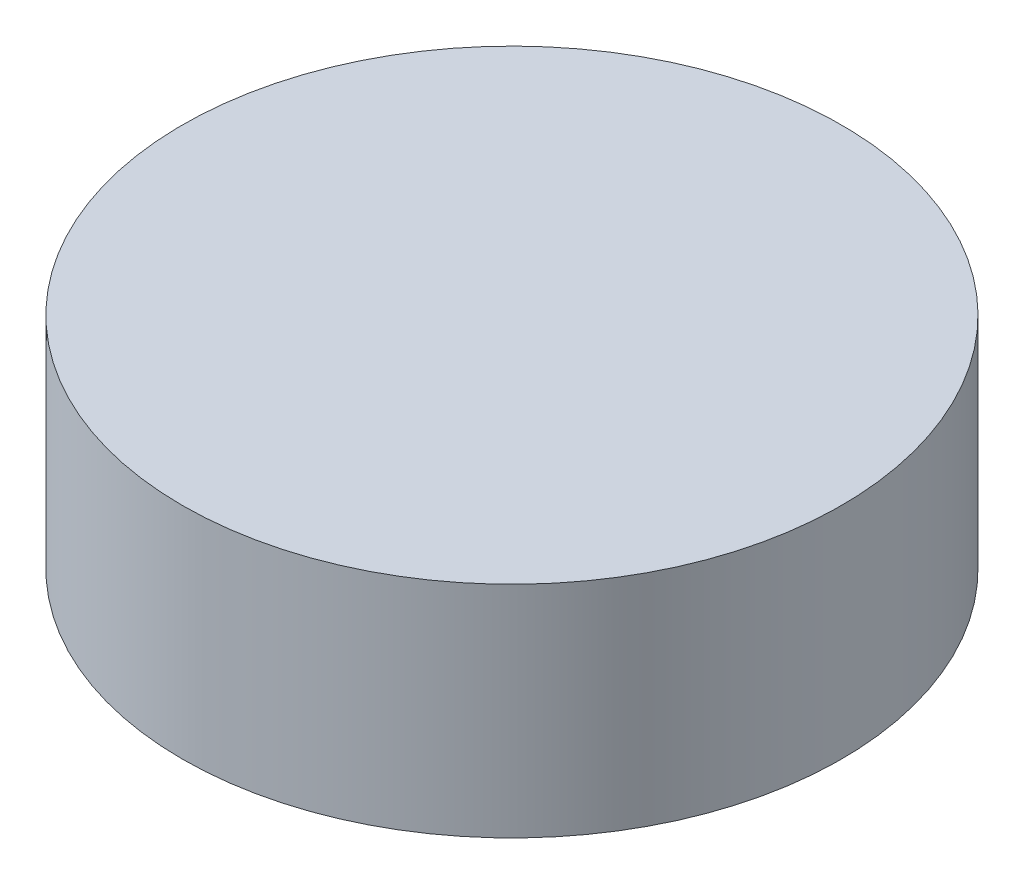
SolidWorks part; units mm, degrees
ref_plane "Alzado" through (0, 0, 0) normal (0, 0, 1) x (1, 0, 0)
ref_plane "Planta" through (0, 0, 0) normal (0, 1, 0) x (1, 0, 0)
ref_plane "Vista lateral" through (0, 0, 0) normal (1, 0, 0) x (0, 0, -1)
sketch "Sketch2" plane through (0, 0, 0) normal (0, 1, 0) x (1, 0, 0)
  circle A0 centre (0, 0) radius 7.5
  dimension "D1" = 15
extrude "Boss-Extrude1" add sketch "Sketch2" along normal blind 5
